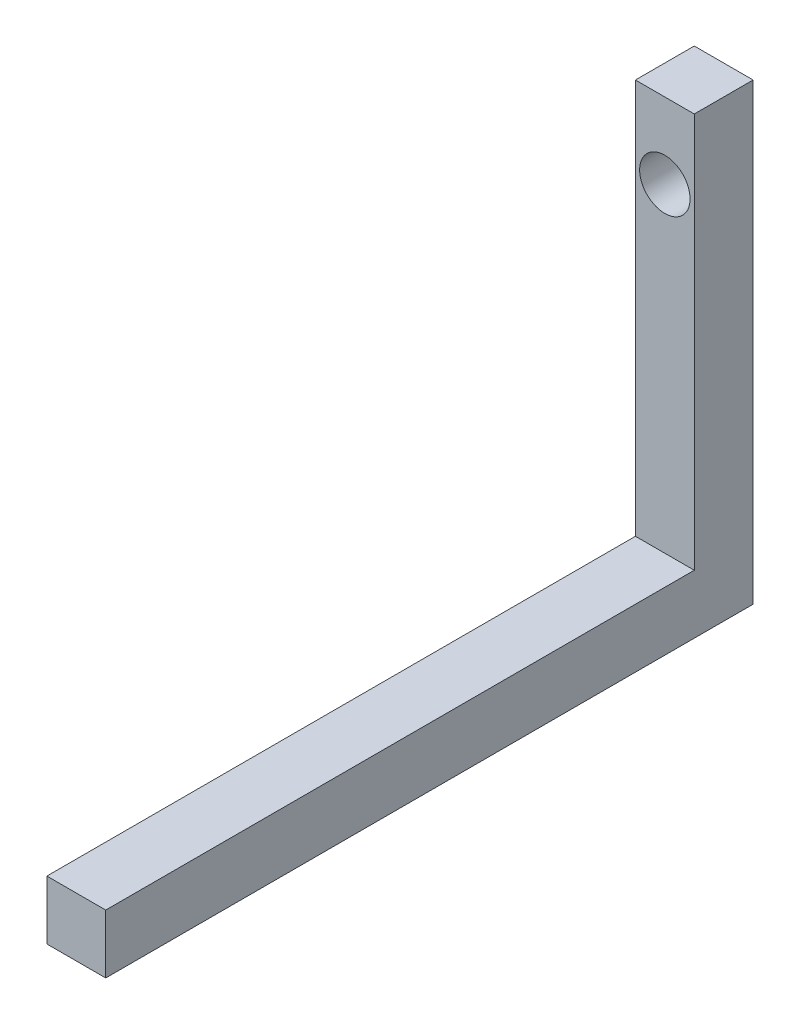
SolidWorks part; units mm, degrees
material "Pino"
ref_plane "Alzado" through (0, 0, 0) normal (0, 0, 1) x (1, 0, 0)
ref_plane "Planta" through (0, 0, 0) normal (0, 1, 0) x (1, 0, 0)
ref_plane "Vista lateral" through (0, 0, 0) normal (1, 0, 0) x (0, 0, -1)
sketch "Croquis1" plane through (0, 0, 0) normal (0, 0, 1) x (1, 0, 0)
  line L1 (-17.5, -17.5) -> (17.5, -17.5)
  line L2 (-17.5, -17.5) -> (-17.5, 17.5)
  line L3 (-17.5, 17.5) -> (17.5, 17.5)
  line L4 (17.5, -17.5) -> (17.5, 17.5)
  line L5 (-17.5, -17.5) -> (17.5, 17.5) construction
  line L6 (-17.5, 17.5) -> (17.5, -17.5) construction
  point P0 (0, 0)
  dimension "D1" = 35
  dimension "D2" = 35
extrude "Saliente-Extruir1" add sketch "Croquis1" along normal blind 385
sketch "Croquis2" plane through (0, 17.5, 0) normal (0, 1, 0) x (1, 0, 0)
  line L0 (17.5, -385) -> (17.5, 0) construction
  line L1 (-17.5, 0) -> (17.5, 0)
  line L2 (-17.5, 0) -> (-17.5, -35)
  line L3 (-17.5, -35) -> (17.5, -35)
  line L4 (17.5, 0) -> (17.5, -35)
  dimension "D1" = 35
extrude "Saliente-Extruir2" add sketch "Croquis2" along normal blind 235
sketch "Croquis3" plane through (0, 0, 0) normal (0, 0, -1) x (-1, 0, 0)
  circle A0 centre (0, 207.5) radius 15
  dimension "D2" = 30
extrude "Cortar-Extruir1" cut sketch "Croquis3" against normal blind 35
